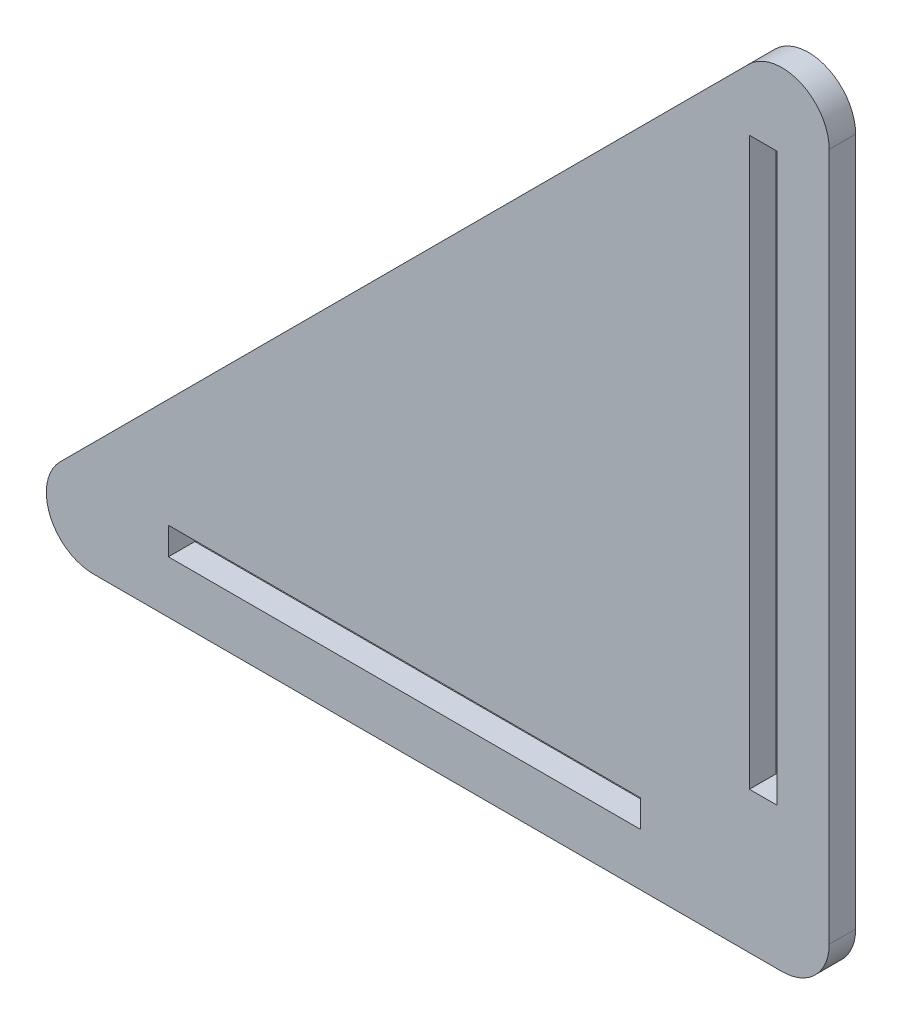
SolidWorks part; units mm, degrees
material "Фанера"
ref_plane "Front Plane" through (0, 0, 0) normal (0, 0, 1) x (1, 0, 0)
ref_plane "Top Plane" through (0, 0, 0) normal (0, 1, 0) x (1, 0, 0)
ref_plane "Right Plane" through (0, 0, 0) normal (1, 0, 0) x (0, 0, -1)
sketch "Эскиз1" plane through (0, 0, 0) normal (0, 0, 1) x (1, 0, 0)
  line L0 (-36.4645, -36.4645) -> (36.4645, 36.4645)
  line L1 (-32.9289, -45) -> (40, -45)
  line L4 (45, -40) -> (45, 32.9289)
  line L5 (-45, -45) -> (45, 45) construction
  line L7 (36.55, -30) -> (39.45, -30)
  line L8 (36.55, -30) -> (36.55, 30)
  line L9 (36.55, 30) -> (39.45, 30)
  line L10 (39.45, -30) -> (39.45, 30)
  line L11 (36.55, -30) -> (39.45, 30) construction
  line L12 (36.55, 30) -> (39.45, -30) construction
  line L13 (-25, -39.45) -> (25, -39.45)
  line L14 (-25, -39.45) -> (-25, -36.55)
  line L15 (-25, -36.55) -> (25, -36.55)
  line L16 (25, -39.45) -> (25, -36.55)
  line L17 (-25, -39.45) -> (25, -36.55) construction
  line L18 (-25, -36.55) -> (25, -39.45) construction
  arc A0 (40, -45) -> (45, -40) centre (40, -40) ccw
  arc A1 (36.4645, 36.4645) -> (45, 32.9289) centre (40, 32.9289) cw
  arc A2 (-32.9289, -45) -> (-36.4645, -36.4645) centre (-32.9289, -40) cw
  point P0 (0, 0)
  point P3 (0, 0)
  point P5 (38, 0)
  point P13 (45, -45)
  point P20 (0, -38)
  point P25 (0, 0)
  dimension "D6" = 5
  dimension "D7" = 5
  dimension "D1" = 90
  dimension "D2" = 2.9
  dimension "D3" = 7
  dimension "D4" = 60
  dimension "D5" = 90
  dimension "D8" = 2.9
  dimension "D9" = 50
  dimension "D10" = 7
extrude "Бобышка-Вытянуть1" add sketch "Эскиз1" along normal mid plane 2.8
